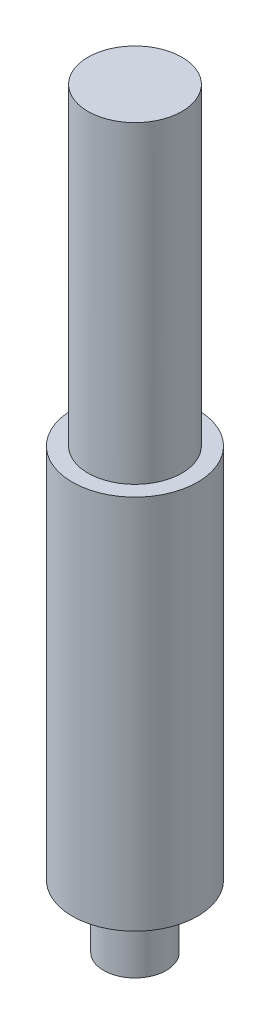
SolidWorks part; units mm, degrees
ref_plane "Front Plane" through (0, 0, 0) normal (0, 0, 1) x (1, 0, 0)
ref_plane "Top Plane" through (0, 0, 0) normal (0, 1, 0) x (1, 0, 0)
ref_plane "Right Plane" through (0, 0, 0) normal (1, 0, 0) x (0, 0, -1)
sketch "Sketch1" plane through (0, 0, 0) normal (0, 1, 0) x (1, 0, 0)
  circle A0 centre (0, 0) radius 9.525
  dimension "D1" = 19.05
extrude "Boss-Extrude1" add sketch "Sketch1" along normal blind 63.5
sketch "Sketch2" plane through (0, 0, 0) normal (0, -1, 0) x (1, 0, 0)
  circle A0 centre (0, 0) radius 12.7
  dimension "D1" = 25.4
extrude "Boss-Extrude2" add sketch "Sketch2" along normal blind 76.2
sketch "Sketch3" plane through (0, -76.2, 0) normal (0, -1, 0) x (1, 0, 0)
  circle A0 centre (0, 0) radius 6.35
  dimension "D1" = 12.7
extrude "Boss-Extrude3" add sketch "Sketch3" along normal blind 12.7
